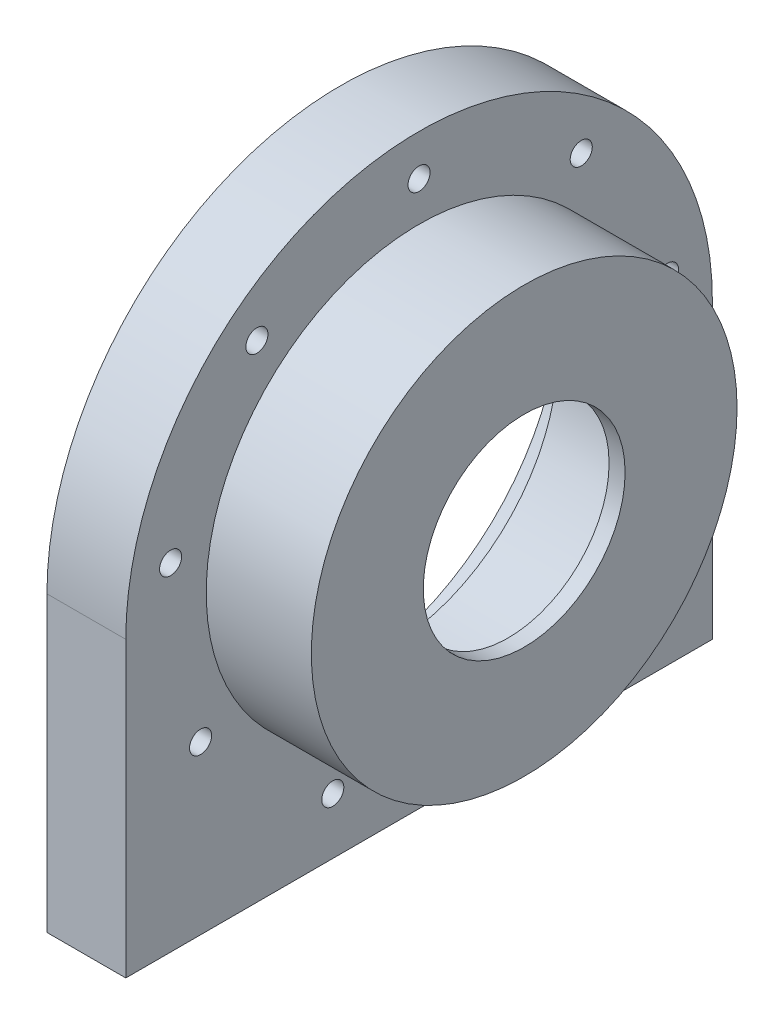
SolidWorks part; units mm, degrees
material "6061-T6 (SS)"
ref_plane "Front Plane" through (0, 0, 0) normal (0, 0, 1) x (1, 0, 0)
ref_plane "Top Plane" through (0, 0, 0) normal (0, 1, 0) x (1, 0, 0)
ref_plane "Right Plane" through (0, 0, 0) normal (1, 0, 0) x (0, 0, -1)
sketch "Sketch1" plane through (0, 0, 0) normal (1, 0, 0) x (0, 0, -1)
  line L0 (0, 0) -> (0, 31) construction
  line L1 (0, 0) -> (31, 0) construction
  line L2 (0, 0) -> (-31, 0) construction
  line L3 (0, 0) -> (0, -31) construction
  line L4 (0, 0) -> (-26.8468, -15.5) construction
  line L5 (0, 0) -> (15.5, -26.8468) construction
  line L6 (0, 0) -> (-15.5, -26.8468) construction
  line L7 (0, 0) -> (15.5, 26.8468) construction
  line L8 (0, 0) -> (-15.5, 26.8468) construction
  line L9 (0, 0) -> (-26.8468, 15.5) construction
  line L10 (0, 0) -> (26.8468, -15.5) construction
  line L11 (0, 0) -> (26.8468, 15.5) construction
  line L12 (46.5, 0) -> (46.5, -46.5)
  line L13 (46.5, -46.5) -> (-46.5, -46.5)
  line L14 (-46.5, 0) -> (-46.5, -46.5)
  circle A0 centre (0, 0) radius 35 construction
  circle A1 centre (0, 0) radius 31 construction
  circle A2 centre (0, 0) radius 27
  circle A3 centre (15.5, 26.8468) radius 1.75
  circle A4 centre (0, 31) radius 1.75
  circle A5 centre (-15.5, 26.8468) radius 1.75
  circle A6 centre (-31, 0) radius 1.75
  circle A7 centre (-26.8468, -15.5) radius 1.75
  circle A8 centre (-15.5, -26.8468) radius 1.75
  circle A9 centre (0, -31) radius 1.75
  circle A10 centre (15.5, -26.8468) radius 1.75
  circle A11 centre (26.8468, -15.5) radius 1.75
  circle A12 centre (31, 0) radius 1.75
  circle A13 centre (26.8468, 15.5) radius 1.75
  circle A14 centre (-26.8468, 15.5) radius 1.75
  circle A15 centre (0, 0) radius 46.5 construction
  arc A16 (46.5, 0) -> (-46.5, 0) centre (0, 0) ccw
  circle A17 centre (0, 40) radius 1.75
  circle A18 centre (25.7115, 30.6418) radius 1.75
  circle A19 centre (39.3923, 6.9459) radius 1.75
  circle A20 centre (34.641, -20) radius 1.75
  circle A21 centre (13.6808, -37.5877) radius 1.75
  circle A22 centre (-13.6808, -37.5877) radius 1.75
  circle A23 centre (-34.641, -20) radius 1.75
  circle A24 centre (-39.3923, 6.9459) radius 1.75
  circle A25 centre (-25.7115, 30.6418) radius 1.75
  point P54 (0, 0)
  dimension "D1" = 70
  dimension "D2" = 62
  dimension "D3" = 54
  dimension "D12" = 3.5
  dimension "D13" = 3.5
  dimension "D14" = 3.5
  dimension "D15" = 3.5
  dimension "D16" = 3.5
  dimension "D17" = 3.5
  dimension "D18" = 3.5
  dimension "D19" = 3.5
  dimension "D20" = 3.5
  dimension "D21" = 3.5
  dimension "D22" = 3.5
  dimension "D23" = 3.5
  dimension "D24" = 93
  dimension "D25" = 40
  dimension "D26" = 3.5
  dimension "D4" = 30
  dimension "D5" = 30
  dimension "D6" = 30
  dimension "D7" = 30
  dimension "D8" = 30
  dimension "D9" = 30
  dimension "D10" = 30
  dimension "D11" = 30
  dimension "D27" = 9
extrude "Boss-Extrude1" add sketch "Sketch1" along normal blind 12.5
sketch "Sketch6" plane through (0, 0, 0) normal (-1, 0, 0) x (0, 0, 1)
  circle A0 centre (0, 0) radius 35
  dimension "D1" = 70
extrude "Cut-Extrude3" cut sketch "Sketch6" against normal blind 7.5
sketch "Sketch7" plane through (12.5, 0, 0) normal (1, 0, 0) x (0, 0, -1)
  circle A1 centre (0, 0) radius 27
  circle A2 centre (0, 0) radius 33.7478
extrude "Boss-Extrude4" add sketch "Sketch7" along normal blind 14.1258
sketch "Sketch8" plane through (26.6258, 0, 0) normal (1, 0, 0) x (0, 0, -1)
  circle A0 centre (0, 0) radius 33.7478
  circle A1 centre (0, 0) radius 16
  dimension "D1" = 32
extrude "Boss-Extrude5" add sketch "Sketch8" along normal blind 2.54
sketch "Sketch9" plane through (0, -46.5, 0) normal (0, -1, 0) x (1, 0, 0)
  line L0 (12.5, 46.5) -> (0, 46.5) construction
  circle A0 centre (6.25, 37.338) radius 2.5
  circle A1 centre (6.25, 24.892) radius 2.5
  circle A2 centre (6.25, 12.446) radius 2.5
  circle A3 centre (6.25, 0) radius 2.5
  circle A4 centre (6.25, -12.446) radius 2.5
  circle A5 centre (6.25, -24.892) radius 2.5
  circle A6 centre (6.25, -37.338) radius 2.5
  dimension "D1" = 9.162
  dimension "D2" = 5
  dimension "D3" = 7
extrude "Cut-Extrude4" cut sketch "Sketch9" against normal blind 5
